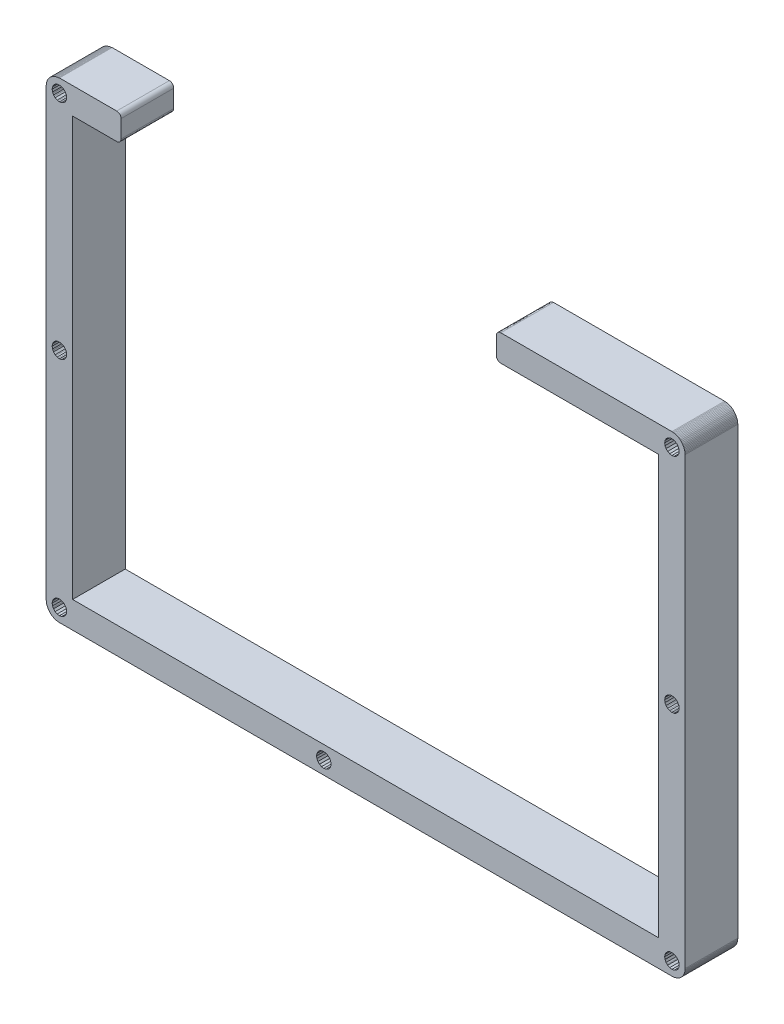
SolidWorks part; units mm, degrees
ref_plane "Front" through (0, 0, 0) normal (0, 0, 1) x (1, 0, 0)
ref_plane "Top" through (0, 0, 0) normal (0, 1, 0) x (1, 0, 0)
ref_plane "Right" through (0, 0, 0) normal (1, 0, 0) x (0, 0, -1)
sketch "Model" plane through (0, 0, 0) normal (0, 0, 1) x (1, 0, 0)
  line L0 (149.1245, 108.8906) -> (148.8893, 108.43)
  line L1 (148.8893, 108.43) -> (148.5236, 108.0643)
  line L2 (148.5236, 108.0643) -> (148.063, 107.8291)
  line L3 (148.063, 107.8291) -> (147.5532, 107.7482)
  line L4 (147.5532, 107.7482) -> (147.0428, 107.8291)
  line L5 (147.0428, 107.8291) -> (146.5821, 108.0643)
  line L6 (146.5821, 108.0643) -> (146.2165, 108.43)
  line L7 (146.2165, 108.43) -> (145.9812, 108.8906)
  line L8 (145.9812, 108.8906) -> (145.901, 109.4014)
  line L9 (145.901, 109.4014) -> (145.9812, 109.9112)
  line L10 (145.9812, 109.9112) -> (146.2165, 110.3715)
  line L11 (146.2165, 110.3715) -> (146.5821, 110.7371)
  line L12 (146.5821, 110.7371) -> (147.0428, 110.9724)
  line L13 (147.0428, 110.9724) -> (147.5532, 111.0526)
  line L14 (147.5532, 111.0526) -> (148.063, 110.9724)
  line L15 (148.063, 110.9724) -> (148.5236, 110.7371)
  line L16 (148.5236, 110.7371) -> (148.8893, 110.3715)
  line L17 (148.8893, 110.3715) -> (149.1245, 109.9112)
  line L18 (149.1245, 109.9112) -> (149.2058, 109.4004)
  line L19 (149.2058, 109.4004) -> (149.1245, 108.8906)
  line L20 (149.1245, 58.1953) -> (148.8893, 57.7347)
  line L21 (148.8893, 57.7347) -> (148.5236, 57.3694)
  line L22 (148.5236, 57.3694) -> (148.063, 57.1349)
  line L23 (148.063, 57.1349) -> (147.5532, 57.054)
  line L24 (147.5532, 57.054) -> (147.0428, 57.1349)
  line L25 (147.0428, 57.1349) -> (146.5821, 57.3694)
  line L26 (146.5821, 57.3694) -> (146.2165, 57.7347)
  line L27 (146.2165, 57.7347) -> (145.9812, 58.1953)
  line L28 (145.9812, 58.1953) -> (145.901, 58.7062)
  line L29 (145.901, 58.7062) -> (145.9812, 59.217)
  line L30 (145.9812, 59.217) -> (146.2165, 59.6776)
  line L31 (146.2165, 59.6776) -> (146.5821, 60.0429)
  line L32 (146.5821, 60.0429) -> (147.0428, 60.2771)
  line L33 (147.0428, 60.2771) -> (147.5532, 60.3584)
  line L34 (147.5532, 60.3584) -> (148.063, 60.2771)
  line L35 (148.063, 60.2771) -> (148.5236, 60.0429)
  line L36 (148.5236, 60.0429) -> (148.8893, 59.6776)
  line L37 (148.8893, 59.6776) -> (149.1245, 59.217)
  line L38 (149.1245, 59.217) -> (149.2058, 58.7062)
  line L39 (149.2058, 58.7062) -> (149.1245, 58.1953)
  line L40 (149.1245, 7.5011) -> (148.8893, 7.0405)
  line L41 (148.8893, 7.0405) -> (148.5236, 6.6752)
  line L42 (148.5236, 6.6752) -> (148.063, 6.4399)
  line L43 (148.063, 6.4399) -> (147.5532, 6.3587)
  line L44 (147.5532, 6.3587) -> (147.0428, 6.4399)
  line L45 (147.0428, 6.4399) -> (146.5821, 6.6752)
  line L46 (146.5821, 6.6752) -> (146.2165, 7.0405)
  line L47 (146.2165, 7.0405) -> (145.9812, 7.5011)
  line L48 (145.9812, 7.5011) -> (145.901, 8.0119)
  line L49 (145.901, 8.0119) -> (145.9812, 8.5217)
  line L50 (145.9812, 8.5217) -> (146.2165, 8.9823)
  line L51 (146.2165, 8.9823) -> (146.5821, 9.3476)
  line L52 (146.5821, 9.3476) -> (147.0428, 9.5832)
  line L53 (147.0428, 9.5832) -> (147.5532, 9.6641)
  line L54 (147.5532, 9.6641) -> (148.063, 9.5832)
  line L55 (148.063, 9.5832) -> (148.5236, 9.3476)
  line L56 (148.5236, 9.3476) -> (148.8893, 8.9823)
  line L57 (148.8893, 8.9823) -> (149.1245, 8.5217)
  line L58 (149.1245, 8.5217) -> (149.2058, 8.0119)
  line L59 (149.2058, 8.0119) -> (149.1245, 7.5011)
  line L60 (69.8152, 7.5011) -> (69.581, 7.0405)
  line L61 (69.581, 7.0405) -> (69.2154, 6.6752)
  line L62 (69.2154, 6.6752) -> (68.7547, 6.4399)
  line L63 (68.7547, 6.4399) -> (68.2442, 6.3587)
  line L64 (68.2442, 6.3587) -> (67.7334, 6.4399)
  line L65 (67.7334, 6.4399) -> (67.2728, 6.6752)
  line L66 (67.2728, 6.6752) -> (66.9072, 7.0405)
  line L67 (66.9072, 7.0405) -> (66.6729, 7.5011)
  line L68 (66.6729, 7.5011) -> (66.592, 8.0119)
  line L69 (66.592, 8.0119) -> (66.6729, 8.5217)
  line L70 (66.6729, 8.5217) -> (66.9072, 8.9823)
  line L71 (66.9072, 8.9823) -> (67.2728, 9.3476)
  line L72 (67.2728, 9.3476) -> (67.7334, 9.5832)
  line L73 (67.7334, 9.5832) -> (68.2442, 9.6641)
  line L74 (68.2442, 9.6641) -> (68.7547, 9.5832)
  line L75 (68.7547, 9.5832) -> (69.2154, 9.3476)
  line L76 (69.2154, 9.3476) -> (69.581, 8.9823)
  line L77 (69.581, 8.9823) -> (69.8152, 8.5217)
  line L78 (69.8152, 8.5217) -> (69.8964, 8.0119)
  line L79 (69.8964, 8.0119) -> (69.8152, 7.5011)
  line L80 (9.583, 108.8906) -> (9.3477, 108.43)
  line L81 (9.3477, 108.43) -> (8.9824, 108.0643)
  line L82 (8.9824, 108.0643) -> (8.5218, 107.8291)
  line L83 (8.5218, 107.8291) -> (8.0109, 107.7482)
  line L84 (8.0109, 107.7482) -> (7.5012, 107.8291)
  line L85 (7.5012, 107.8291) -> (7.0405, 108.0643)
  line L86 (7.0405, 108.0643) -> (6.6753, 108.43)
  line L87 (6.6753, 108.43) -> (6.4396, 108.8906)
  line L88 (6.4396, 108.8906) -> (6.3587, 109.4014)
  line L89 (6.3587, 109.4014) -> (6.4396, 109.9112)
  line L90 (6.4396, 109.9112) -> (6.6753, 110.3715)
  line L91 (6.6753, 110.3715) -> (7.0405, 110.7371)
  line L92 (7.0405, 110.7371) -> (7.5012, 110.9724)
  line L93 (7.5012, 110.9724) -> (8.012, 111.0526)
  line L94 (8.012, 111.0526) -> (8.5218, 110.9724)
  line L95 (8.5218, 110.9724) -> (8.9824, 110.7371)
  line L96 (8.9824, 110.7371) -> (9.3477, 110.3715)
  line L97 (9.3477, 110.3715) -> (9.583, 109.9112)
  line L98 (9.583, 109.9112) -> (9.6642, 109.4004)
  line L99 (9.6642, 109.4004) -> (9.583, 108.8906)
  line L100 (9.583, 58.1953) -> (9.3477, 57.7347)
  line L101 (9.3477, 57.7347) -> (8.9824, 57.3694)
  line L102 (8.9824, 57.3694) -> (8.5218, 57.1349)
  line L103 (8.5218, 57.1349) -> (8.0109, 57.054)
  line L104 (8.0109, 57.054) -> (7.5012, 57.1349)
  line L105 (7.5012, 57.1349) -> (7.0405, 57.3694)
  line L106 (7.0405, 57.3694) -> (6.6753, 57.7347)
  line L107 (6.6753, 57.7347) -> (6.4396, 58.1953)
  line L108 (6.4396, 58.1953) -> (6.3588, 58.7062)
  line L109 (6.3588, 58.7062) -> (6.4396, 59.217)
  line L110 (6.4396, 59.217) -> (6.6753, 59.6776)
  line L111 (6.6753, 59.6776) -> (7.0405, 60.0429)
  line L112 (7.0405, 60.0429) -> (7.5012, 60.2771)
  line L113 (7.5012, 60.2771) -> (8.012, 60.3584)
  line L114 (8.012, 60.3584) -> (8.5218, 60.2771)
  line L115 (8.5218, 60.2771) -> (8.9824, 60.0429)
  line L116 (8.9824, 60.0429) -> (9.3477, 59.6776)
  line L117 (9.3477, 59.6776) -> (9.583, 59.217)
  line L118 (9.583, 59.217) -> (9.6642, 58.7062)
  line L119 (9.6642, 58.7062) -> (9.583, 58.1953)
  line L120 (9.583, 7.5011) -> (9.3477, 7.0405)
  line L121 (9.3477, 7.0405) -> (8.9824, 6.6752)
  line L122 (8.9824, 6.6752) -> (8.5218, 6.4399)
  line L123 (8.5218, 6.4399) -> (8.0109, 6.3587)
  line L124 (8.0109, 6.3587) -> (7.5012, 6.4399)
  line L125 (7.5012, 6.4399) -> (7.0405, 6.6752)
  line L126 (7.0405, 6.6752) -> (6.6753, 7.0405)
  line L127 (6.6753, 7.0405) -> (6.4396, 7.5011)
  line L128 (6.4396, 7.5011) -> (6.3588, 8.0119)
  line L129 (6.3588, 8.0119) -> (6.4396, 8.5217)
  line L130 (6.4396, 8.5217) -> (6.6753, 8.9823)
  line L131 (6.6753, 8.9823) -> (7.0405, 9.3476)
  line L132 (7.0405, 9.3476) -> (7.5012, 9.5832)
  line L133 (7.5012, 9.5832) -> (8.012, 9.6641)
  line L134 (8.012, 9.6641) -> (8.5218, 9.5832)
  line L135 (8.5218, 9.5832) -> (8.9824, 9.3476)
  line L136 (8.9824, 9.3476) -> (9.3477, 8.9823)
  line L137 (9.3477, 8.9823) -> (9.583, 8.5217)
  line L138 (9.583, 8.5217) -> (9.6642, 8.0119)
  line L139 (9.6642, 8.0119) -> (9.583, 7.5011)
  line L140 (150.5469, 109.6382) -> (150.5201, 109.8724)
  line L141 (150.5201, 109.8724) -> (150.4738, 110.1038)
  line L142 (150.4738, 110.1038) -> (150.4099, 110.331)
  line L143 (150.4099, 110.331) -> (150.3276, 110.5525)
  line L144 (150.3276, 110.5525) -> (150.2294, 110.7658)
  line L145 (150.2294, 110.7658) -> (150.113, 110.9731)
  line L146 (150.113, 110.9731) -> (149.9854, 111.1649)
  line L147 (149.9854, 111.1649) -> (149.8391, 111.3504)
  line L148 (149.8391, 111.3504) -> (149.6791, 111.5235)
  line L149 (149.6791, 111.5235) -> (149.502, 111.7375)
  line L150 (149.502, 111.7375) -> (149.3169, 111.8838)
  line L151 (149.3169, 111.8838) -> (149.1205, 112.0141)
  line L152 (149.1205, 112.0141) -> (148.9142, 112.1303)
  line L153 (148.9142, 112.1303) -> (148.7012, 112.2282)
  line L154 (148.7012, 112.2282) -> (148.4797, 112.3105)
  line L155 (148.4797, 112.3105) -> (148.2525, 112.3744)
  line L156 (148.2525, 112.3744) -> (148.0212, 112.4207)
  line L157 (148.0212, 112.4207) -> (147.787, 112.4476)
  line L158 (147.787, 112.4476) -> (147.5513, 112.4568)
  line L159 (147.5513, 112.4568) -> (108.5726, 112.4568)
  line L160 (107.569, 111.4528) -> (107.569, 107.45)
  line L161 (108.5705, 106.4485) -> (144.5476, 106.4485)
  line L162 (144.5476, 106.4485) -> (144.5476, 11.0683)
  line L163 (144.5476, 11.0683) -> (11.0142, 11.0683)
  line L164 (11.0142, 11.0683) -> (11.0142, 106.4485)
  line L165 (11.0142, 106.4485) -> (21.0606, 106.4485)
  line L166 (22.0585, 107.4465) -> (22.0585, 111.4599)
  line L167 (21.0606, 112.4578) -> (8.0101, 112.4578)
  line L168 (8.0101, 112.4578) -> (7.7746, 112.3953)
  line L169 (7.7746, 112.3953) -> (7.54, 112.3685)
  line L170 (7.54, 112.3685) -> (7.309, 112.3222)
  line L171 (7.309, 112.3222) -> (7.0815, 112.2583)
  line L172 (7.0815, 112.2583) -> (6.8604, 112.176)
  line L173 (6.8604, 112.176) -> (6.647, 112.0781)
  line L174 (6.647, 112.0781) -> (6.4407, 111.9619)
  line L175 (6.4407, 111.9619) -> (6.2443, 111.8315)
  line L176 (6.2443, 111.8315) -> (6.0592, 111.6853)
  line L177 (6.0592, 111.6853) -> (5.8861, 111.5252)
  line L178 (5.8861, 111.5252) -> (5.7257, 111.3521)
  line L179 (5.7257, 111.3521) -> (5.5794, 111.1667)
  line L180 (5.5794, 111.1667) -> (5.4494, 110.9706)
  line L181 (5.4494, 110.9706) -> (5.3332, 110.7643)
  line L182 (5.3332, 110.7643) -> (5.235, 110.5509)
  line L183 (5.235, 110.5509) -> (5.1531, 110.3294)
  line L184 (5.1531, 110.3294) -> (5.0888, 110.1023)
  line L185 (5.0888, 110.1023) -> (5.0429, 109.8709)
  line L186 (5.0429, 109.8709) -> (5.0157, 109.6367)
  line L187 (5.0157, 109.6367) -> (5.0068, 109.4004)
  line L188 (5.0068, 109.4004) -> (5.0068, 8.0119)
  line L189 (5.0068, 8.0119) -> (5.0167, 7.7756)
  line L190 (5.0167, 7.7756) -> (5.0439, 7.5414)
  line L191 (5.0439, 7.5414) -> (5.0898, 7.31)
  line L192 (5.0898, 7.31) -> (5.1541, 7.0825)
  line L193 (5.1541, 7.0825) -> (5.2361, 6.8614)
  line L194 (5.2361, 6.8614) -> (5.3343, 6.648)
  line L195 (5.3343, 6.648) -> (5.4505, 6.4417)
  line L196 (5.4505, 6.4417) -> (5.5805, 6.2456)
  line L197 (5.5805, 6.2456) -> (5.7268, 6.0602)
  line L198 (5.7268, 6.0602) -> (5.8871, 5.8871)
  line L199 (5.8871, 5.8871) -> (6.0602, 5.7267)
  line L200 (6.0602, 5.7267) -> (6.2454, 5.5804)
  line L201 (6.2454, 5.5804) -> (6.4418, 5.4504)
  line L202 (6.4418, 5.4504) -> (6.6481, 5.3342)
  line L203 (6.6481, 5.3342) -> (6.8614, 5.236)
  line L204 (6.8614, 5.236) -> (7.0826, 5.1541)
  line L205 (7.0826, 5.1541) -> (7.3101, 5.0901)
  line L206 (7.3101, 5.0901) -> (7.5411, 5.0438)
  line L207 (7.5411, 5.0438) -> (7.7757, 5.017)
  line L208 (7.7757, 5.017) -> (8.012, 5.0078)
  line L209 (8.012, 5.0078) -> (147.5525, 5.0078)
  line L210 (147.5525, 5.0078) -> (147.796, 5.0184)
  line L211 (147.796, 5.0184) -> (148.0302, 5.0452)
  line L212 (148.0302, 5.0452) -> (148.2616, 5.0915)
  line L213 (148.2616, 5.0915) -> (148.4887, 5.1554)
  line L214 (148.4887, 5.1554) -> (148.7102, 5.2374)
  line L215 (148.7102, 5.2374) -> (148.9232, 5.3356)
  line L216 (148.9232, 5.3356) -> (149.1295, 5.4518)
  line L217 (149.1295, 5.4518) -> (149.3259, 5.5818)
  line L218 (149.3259, 5.5818) -> (149.511, 5.7281)
  line L219 (149.511, 5.7281) -> (149.6845, 5.8885)
  line L220 (149.6845, 5.8885) -> (149.8445, 6.0616)
  line L221 (149.8445, 6.0616) -> (149.9908, 6.247)
  line L222 (149.9908, 6.247) -> (150.114, 6.4417)
  line L223 (150.114, 6.4417) -> (150.2294, 6.6495)
  line L224 (150.2294, 6.6495) -> (150.3276, 6.8629)
  line L225 (150.3276, 6.8629) -> (150.4099, 7.084)
  line L226 (150.4099, 7.084) -> (150.4738, 7.3115)
  line L227 (150.4738, 7.3115) -> (150.5201, 7.5429)
  line L228 (150.5201, 7.5429) -> (150.5469, 7.7771)
  line L229 (150.5469, 7.7771) -> (150.5568, 8.0135)
  line L230 (150.5568, 8.0135) -> (150.5568, 109.4019)
  line L231 (150.5568, 109.4019) -> (150.5469, 109.6382)
  line L232 (148.8892, 8.9823) -> (148.5236, 9.3479)
  line L233 (148.5236, 9.3479) -> (148.063, 9.5832)
  line L234 (148.063, 9.5832) -> (147.5535, 9.6641)
  line L235 (147.5535, 9.6641) -> (147.0427, 9.5832)
  line L236 (147.0427, 9.5832) -> (146.5821, 9.3479)
  line L237 (146.5821, 9.3479) -> (146.2165, 8.9823)
  line L238 (146.2165, 8.9823) -> (145.9812, 8.5216)
  line L239 (145.9812, 8.5216) -> (145.901, 8.0119)
  line L240 (145.901, 8.0119) -> (145.9812, 7.5014)
  line L241 (145.9812, 7.5014) -> (146.2165, 7.0408)
  line L242 (146.2165, 7.0408) -> (146.5821, 6.6751)
  line L243 (146.5821, 6.6751) -> (147.0427, 6.4399)
  line L244 (147.0427, 6.4399) -> (147.5535, 6.3586)
  line L245 (147.5535, 6.3586) -> (148.063, 6.4399)
  line L246 (148.063, 6.4399) -> (148.5236, 6.6751)
  line L247 (148.5236, 6.6751) -> (148.8892, 7.0408)
  line L248 (148.8892, 7.0408) -> (149.1245, 7.5014)
  line L249 (149.1245, 7.5014) -> (149.2057, 8.0119)
  line L250 (149.2057, 8.0119) -> (149.1245, 8.5216)
  line L251 (149.1245, 8.5216) -> (148.8892, 8.9823)
  line L252 (69.581, 8.9823) -> (69.2154, 9.3479)
  line L253 (69.2154, 9.3479) -> (68.7547, 9.5832)
  line L254 (68.7547, 9.5832) -> (68.2442, 9.6641)
  line L255 (68.2442, 9.6641) -> (67.7334, 9.5832)
  line L256 (67.7334, 9.5832) -> (67.2728, 9.3479)
  line L257 (67.2728, 9.3479) -> (66.9075, 8.9823)
  line L258 (66.9075, 8.9823) -> (66.6729, 8.5216)
  line L259 (66.6729, 8.5216) -> (66.592, 8.0119)
  line L260 (66.592, 8.0119) -> (66.6729, 7.5014)
  line L261 (66.6729, 7.5014) -> (66.9075, 7.0408)
  line L262 (66.9075, 7.0408) -> (67.2728, 6.6751)
  line L263 (67.2728, 6.6751) -> (67.7334, 6.4399)
  line L264 (67.7334, 6.4399) -> (68.2442, 6.3586)
  line L265 (68.2442, 6.3586) -> (68.7547, 6.4399)
  line L266 (68.7547, 6.4399) -> (69.2154, 6.6751)
  line L267 (69.2154, 6.6751) -> (69.581, 7.0408)
  line L268 (69.581, 7.0408) -> (69.8152, 7.5014)
  line L269 (69.8152, 7.5014) -> (69.8964, 8.0119)
  line L270 (69.8964, 8.0119) -> (69.8152, 8.5216)
  line L271 (69.8152, 8.5216) -> (69.581, 8.9823)
  line L272 (9.3478, 8.9823) -> (8.9821, 9.3479)
  line L273 (8.9821, 9.3479) -> (8.5215, 9.5832)
  line L274 (8.5215, 9.5832) -> (8.0121, 9.6641)
  line L275 (8.0121, 9.6641) -> (7.5013, 9.5832)
  line L276 (7.5013, 9.5832) -> (7.0406, 9.3479)
  line L277 (7.0406, 9.3479) -> (6.675, 8.9823)
  line L278 (6.675, 8.9823) -> (6.4397, 8.5216)
  line L279 (6.4397, 8.5216) -> (6.3588, 8.0119)
  line L280 (6.3588, 8.0119) -> (6.4397, 7.5014)
  line L281 (6.4397, 7.5014) -> (6.675, 7.0408)
  line L282 (6.675, 7.0408) -> (7.0406, 6.6751)
  line L283 (7.0406, 6.6751) -> (7.5013, 6.4399)
  line L284 (7.5013, 6.4399) -> (8.011, 6.3586)
  line L285 (8.011, 6.3586) -> (8.5215, 6.4399)
  line L286 (8.5215, 6.4399) -> (8.9821, 6.6751)
  line L287 (8.9821, 6.6751) -> (9.3478, 7.0408)
  line L288 (9.3478, 7.0408) -> (9.583, 7.5014)
  line L289 (9.583, 7.5014) -> (9.6643, 8.0119)
  line L290 (9.6643, 8.0119) -> (9.583, 8.5216)
  line L291 (9.583, 8.5216) -> (9.3478, 8.9823)
  line L292 (148.8892, 59.6774) -> (148.5236, 60.0431)
  line L293 (148.5236, 60.0431) -> (148.063, 60.2773)
  line L294 (148.063, 60.2773) -> (147.5535, 60.3585)
  line L295 (147.5535, 60.3585) -> (147.0427, 60.2773)
  line L296 (147.0427, 60.2773) -> (146.5821, 60.0431)
  line L297 (146.5821, 60.0431) -> (146.2165, 59.6774)
  line L298 (146.2165, 59.6774) -> (145.9812, 59.2168)
  line L299 (145.9812, 59.2168) -> (145.901, 58.706)
  line L300 (145.901, 58.706) -> (145.9812, 58.1955)
  line L301 (145.9812, 58.1955) -> (146.2165, 57.7349)
  line L302 (146.2165, 57.7349) -> (146.5821, 57.3692)
  line L303 (146.5821, 57.3692) -> (147.0427, 57.135)
  line L304 (147.0427, 57.135) -> (147.5535, 57.0538)
  line L305 (147.5535, 57.0538) -> (148.063, 57.135)
  line L306 (148.063, 57.135) -> (148.5236, 57.3692)
  line L307 (148.5236, 57.3692) -> (148.8892, 57.7349)
  line L308 (148.8892, 57.7349) -> (149.1245, 58.1955)
  line L309 (149.1245, 58.1955) -> (149.2057, 58.706)
  line L310 (149.2057, 58.706) -> (149.1245, 59.2168)
  line L311 (149.1245, 59.2168) -> (148.8892, 59.6774)
  line L312 (9.3478, 59.6774) -> (8.9821, 60.0431)
  line L313 (8.9821, 60.0431) -> (8.5215, 60.2773)
  line L314 (8.5215, 60.2773) -> (8.0121, 60.3585)
  line L315 (8.0121, 60.3585) -> (7.5013, 60.2773)
  line L316 (7.5013, 60.2773) -> (7.0406, 60.0431)
  line L317 (7.0406, 60.0431) -> (6.675, 59.6774)
  line L318 (6.675, 59.6774) -> (6.4397, 59.2168)
  line L319 (6.4397, 59.2168) -> (6.3588, 58.706)
  line L320 (6.3588, 58.706) -> (6.4397, 58.1955)
  line L321 (6.4397, 58.1955) -> (6.675, 57.7349)
  line L322 (6.675, 57.7349) -> (7.0406, 57.3692)
  line L323 (7.0406, 57.3692) -> (7.5013, 57.135)
  line L324 (7.5013, 57.135) -> (8.011, 57.0538)
  line L325 (8.011, 57.0538) -> (8.5215, 57.135)
  line L326 (8.5215, 57.135) -> (8.9821, 57.3692)
  line L327 (8.9821, 57.3692) -> (9.3478, 57.7349)
  line L328 (9.3478, 57.7349) -> (9.583, 58.1955)
  line L329 (9.583, 58.1955) -> (9.6643, 58.706)
  line L330 (9.6643, 58.706) -> (9.583, 59.2168)
  line L331 (9.583, 59.2168) -> (9.3478, 59.6774)
  line L332 (148.8892, 110.3716) -> (148.5235, 110.7372)
  line L333 (148.5235, 110.7372) -> (148.0629, 110.9725)
  line L334 (148.0629, 110.9725) -> (147.5535, 111.0524)
  line L335 (147.5535, 111.0524) -> (147.0427, 110.9722)
  line L336 (147.0427, 110.9722) -> (146.582, 110.7369)
  line L337 (146.582, 110.7369) -> (146.2164, 110.3713)
  line L338 (146.2164, 110.3713) -> (145.9811, 109.9106)
  line L339 (145.9811, 109.9106) -> (145.9009, 109.4009)
  line L340 (145.9009, 109.4009) -> (145.9812, 108.8904)
  line L341 (145.9812, 108.8904) -> (146.2166, 108.4298)
  line L342 (146.2166, 108.4298) -> (146.5822, 108.0642)
  line L343 (146.5822, 108.0642) -> (147.0429, 107.829)
  line L344 (147.0429, 107.829) -> (147.5537, 107.7478)
  line L345 (147.5537, 107.7478) -> (148.0631, 107.8291)
  line L346 (148.0631, 107.8291) -> (148.5237, 108.0644)
  line L347 (148.5237, 108.0644) -> (148.8893, 108.4301)
  line L348 (148.8893, 108.4301) -> (149.1246, 108.8908)
  line L349 (149.1246, 108.8908) -> (149.2057, 109.4002)
  line L350 (149.2057, 109.4002) -> (149.1245, 109.911)
  line L351 (149.1245, 109.911) -> (148.8892, 110.3716)
  line L352 (9.3478, 110.3716) -> (8.9821, 110.7373)
  line L353 (8.9821, 110.7373) -> (8.5215, 110.9725)
  line L354 (8.5215, 110.9725) -> (8.0121, 111.0527)
  line L355 (8.0121, 111.0527) -> (7.5013, 110.9724)
  line L356 (7.5013, 110.9724) -> (7.0406, 110.7373)
  line L357 (7.0406, 110.7373) -> (6.675, 110.3716)
  line L358 (6.675, 110.3716) -> (6.4397, 109.911)
  line L359 (6.4397, 109.911) -> (6.3588, 109.4012)
  line L360 (6.3588, 109.4012) -> (6.4397, 108.8908)
  line L361 (6.4397, 108.8908) -> (6.675, 108.4301)
  line L362 (6.675, 108.4301) -> (7.0406, 108.0645)
  line L363 (7.0406, 108.0645) -> (7.5013, 107.8292)
  line L364 (7.5013, 107.8292) -> (8.011, 107.748)
  line L365 (8.011, 107.748) -> (8.5215, 107.8292)
  line L366 (8.5215, 107.8292) -> (8.9821, 108.0645)
  line L367 (8.9821, 108.0645) -> (9.3478, 108.4301)
  line L368 (9.3478, 108.4301) -> (9.583, 108.8908)
  line L369 (9.583, 108.8908) -> (9.6643, 109.4002)
  line L370 (9.6643, 109.4002) -> (9.583, 109.911)
  line L371 (9.583, 109.911) -> (9.3478, 110.3716)
  spline S0 degree 3 poles (108.5726, 112.4568) (108.0184, 112.4568) (107.569, 112.0074) (107.569, 111.4528) knots 0 0 0 0 1 1 1 1
  spline S1 degree 3 poles (107.569, 107.45) (107.569, 106.8968) (108.0173, 106.4485) (108.5705, 106.4485) knots 0 0 0 0 1 1 1 1
  spline S2 degree 3 poles (21.0606, 106.4485) (21.6117, 106.4485) (22.0585, 106.8954) (22.0585, 107.4465) knots 0 0 0 0 1 1 1 1
  spline S3 degree 3 poles (22.0585, 111.4599) (22.0585, 112.0109) (21.612, 112.4578) (21.0606, 112.4578) knots 0 0 0 0 1 1 1 1
  dimension "D1" = 145.55
  dimension "D2" = 107.45
extrude "Boss-Extrude1" add sketch "Model" along normal blind 12 contours L166 S3 L167 L168 L169 L170 L171 L172 L173 L174 L175 L176 L177 L178 L179 L180 L181 L182 L183 L184 L185 L186 L187 L188 L189 L190 L191 L192 L193 L194 L195 L196 L197 L198 L199 L200 L201 L202 L203 L204 L205 L206 L207 L208 L209 L210 L211 L212 L213 L214 L215
